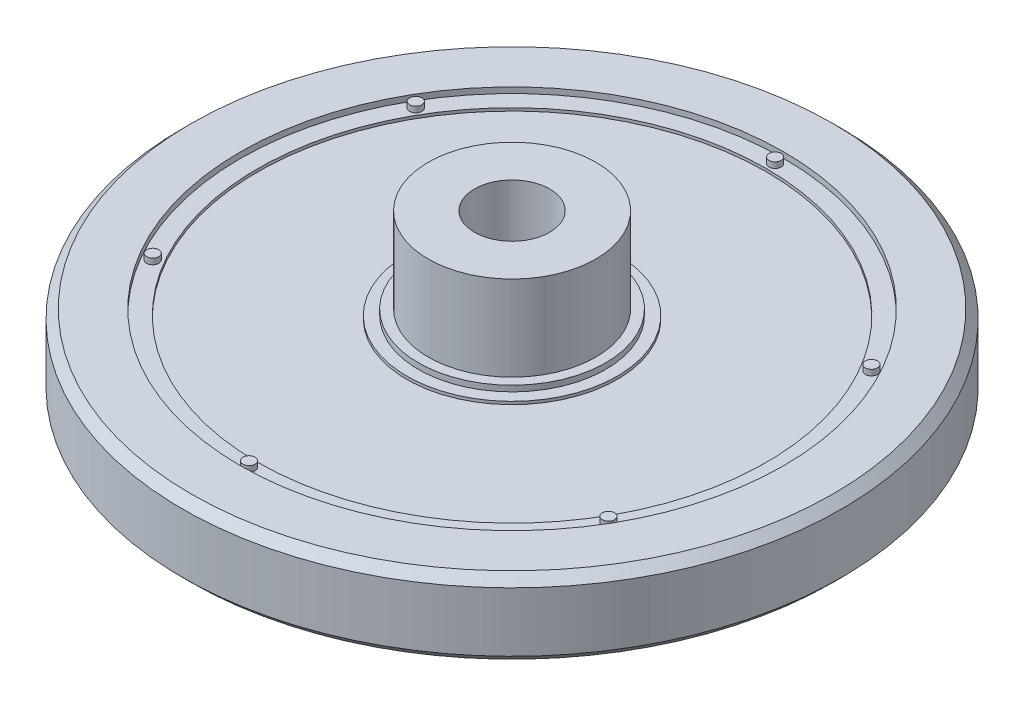
SolidWorks part; units mm, degrees
ref_plane "Front Plane" through (0, 0, 0) normal (0, 0, 1) x (1, 0, 0)
ref_plane "Top Plane" through (0, 0, 0) normal (0, 1, 0) x (1, 0, 0)
ref_plane "Right Plane" through (0, 0, 0) normal (1, 0, 0) x (0, 0, -1)
sketch "Sketch2" plane through (0, 0, 0) normal (0, 0, 1) x (1, 0, 0)
  line L0 (0, 0) -> (0, 5.8561) construction
  line L1 (-1.81, 2.68) -> (-1.81, 4.68)
  line L2 (-1.81, 4.68) -> (-1.56, 4.68)
  line L3 (-1.56, 4.68) -> (-1.56, 6.78)
  line L4 (-1.56, 6.78) -> (-1.3, 6.78)
  line L5 (-1.3, 6.78) -> (-1.3, 9.32)
  line L7 (-3.24, 6.38) -> (-3.24, 6.18)
  line L8 (-3.24, 6.18) -> (-3.64, 6.18)
  line L9 (-3.64, 6.18) -> (-3.64, 6.08)
  line L10 (-3.64, 6.08) -> (-8.8, 6.08)
  line L11 (-8.8, 6.08) -> (-8.8, 6.18)
  line L12 (-8.8, 6.18) -> (-9.4, 6.18)
  line L13 (-9.4, 6.18) -> (-9.4, 6.38)
  line L14 (-9.4, 6.38) -> (-11.1, 6.38)
  line L15 (-11.1, 6.38) -> (-11.4, 6.08)
  line L16 (-11.4, 6.08) -> (-11.4, 4.03)
  line L17 (-11.4, 4.03) -> (-11.1, 3.73)
  line L18 (-11.1, 3.73) -> (-9.4, 3.73)
  line L20 (-2.5, 4.03) -> (-2.5, 2.68)
  line L21 (-2.5, 2.68) -> (-1.81, 2.68)
  line L22 (-3.24, 6.38) -> (-2.9, 6.38)
  line L23 (-2.9, 6.38) -> (-2.9, 9.32)
  line L24 (-2.9, 9.32) -> (-1.3, 9.32)
  line L25 (-2.5, 4.03) -> (-2.61, 4.03)
  line L26 (-2.61, 4.03) -> (-2.61, 4.2891)
  line L27 (-2.61, 4.2891) -> (-2.54, 4.2891)
  line L28 (-2.54, 4.34) -> (-2.54, 4.2891)
  line L29 (-2.54, 4.34) -> (-9.4, 3.73)
  line L30 (-11.4, 5.055) -> (-12.0165, 5.055) construction
  point P28 (0, 0)
  point P30 (0, 0)
  point P31 (0, 0)
  point P32 (0, 0)
  dimension "D1" = 2
  dimension "D2" = 2.1
  dimension "D3" = 2.54
  dimension "D4" = 5.8
  dimension "D5" = 3.12
  dimension "2.6" = 2.6
  dimension "D6" = 3.62
  dimension "D7" = 5
  dimension "D8" = 5.22
  dimension "D9" = 5.08
  dimension "D10" = 2.68
  dimension "D11" = 18.8
  dimension "1.66" = 1.66
  dimension "D12" = 2.65
  dimension "D13" = 3.5
  dimension "D14" = 45
  dimension "D15" = 17.6
  dimension "18.8" = 18.8
  dimension "D16" = 11.4
  dimension "D17" = 45
  dimension "D18" = 2.94
  dimension "D19" = 7.28
  dimension "D20" = 6.48
  dimension "D21" = 11.1
revolve "Revolve1" add sketch "Sketch2" angle 360 about L0
sketch "Sketch3" plane through (0, 6.18, 0) normal (0, 1, 0) x (1, 0, 0)
  circle A0 centre (0, 9.1) radius 0.21
  dimension "D1" = 9.1
  dimension "D2" = 0.42
extrude "Boss-Extrude1" add sketch "Sketch3" along normal blind 0.2
pattern_circular "CirPattern1" count 6 over 360 about axis through (0, 0, 0) along (0, 1, 0) of "Boss-Extrude1"
